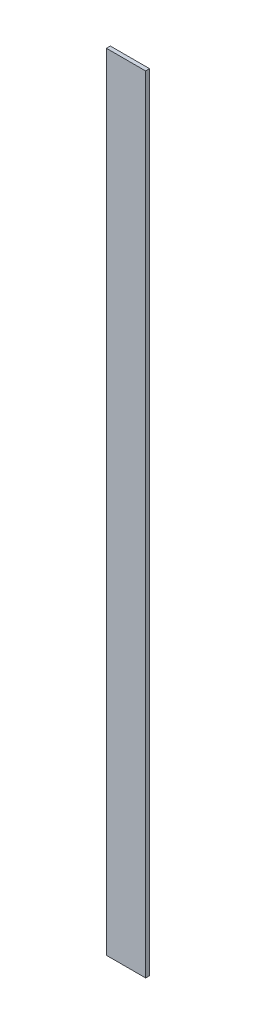
SolidWorks part; units mm, degrees
ref_plane "Front Plane" through (0, 0, 0) normal (0, 0, 1) x (1, 0, 0)
ref_plane "Top Plane" through (0, 0, 0) normal (0, 1, 0) x (1, 0, 0)
ref_plane "Right Plane" through (0, 0, 0) normal (1, 0, 0) x (0, 0, -1)
sketch "Sketch1" plane through (0, 0, 0) normal (0, 0, 1) x (1, 0, 0)
  line L1 (0, 0) -> (60, 0)
  line L2 (0, 0) -> (0, 1200)
  line L3 (0, 1200) -> (60, 1200)
  line L4 (60, 0) -> (60, 1200)
  dimension "D1" = 60
  dimension "D2" = 1200
extrude "Profile" add sketch "Sketch1" along normal blind 6
equation "\"Profile_Depth\"= 6mm"
equation "\"D1@Profile\" = \"Profile_Depth\""
equation "\"Profile_Sketch_1\"= 60mm"
equation "\"D1@Sketch1\" = \"Profile_Sketch_1\""
equation "\"Profile_Sketch_2\"= 1200mm"
equation "\"D2@Sketch1\" = \"Profile_Sketch_2\""
equation "\"EnvelopeWidth\"= 60mm"
equation "\"EnvelopeHeight\"= 1200mm"
